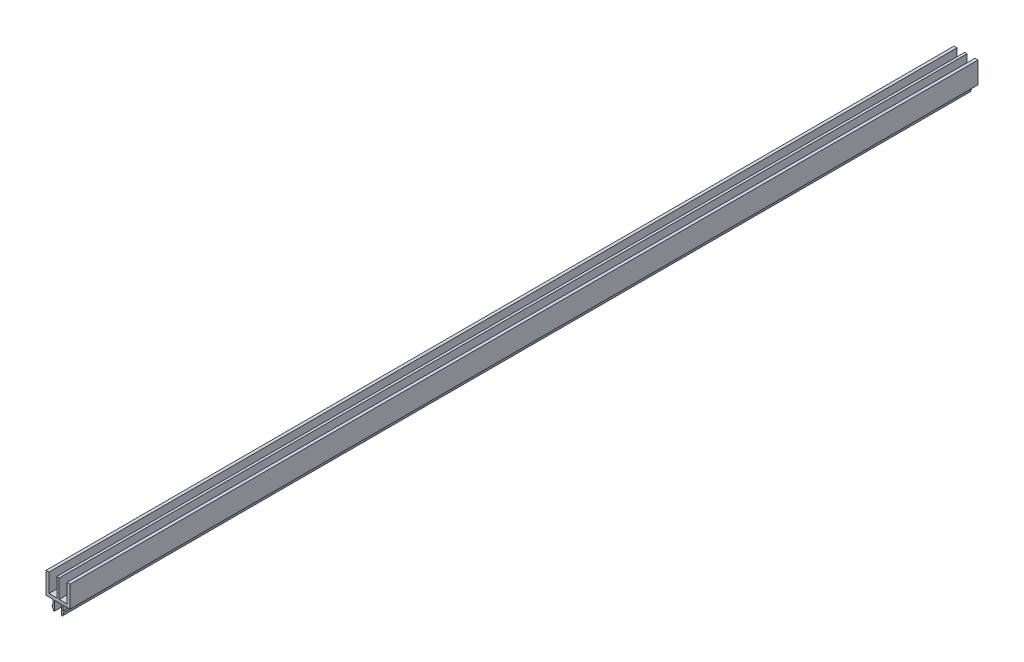
SolidWorks part; units mm, degrees
ref_plane "Plan de face" through (0, 0, 0) normal (0, 0, 1) x (1, 0, 0)
ref_plane "Plan de dessus" through (0, 0, 0) normal (0, 1, 0) x (1, 0, 0)
ref_plane "Plan de droite" through (0, 0, 0) normal (1, 0, 0) x (0, 0, -1)
ref_plane "Plan1" through (0, 0, 50) normal (0, 0, 1) x (1, 0, 0)
sketch "Esquisse1" plane through (0, 0, 50) normal (0, 0, 1) x (1, 0, 0)
  line L0 (-1, 2.5) -> (-7.5, 2.5)
  line L1 (-7.5, 2.5) -> (-7.5, 18)
  line L2 (-7.5, 18) -> (-10, 18)
  line L3 (-10, 18) -> (-10, 0)
  line L4 (-10, 0) -> (-4, 0)
  line L5 (-4, 0) -> (-4, -4.5)
  line L6 (-4, -4.5) -> (-5, -4.5)
  line L7 (-5, -4.5) -> (-3.75, -8)
  line L8 (-3.75, -8) -> (-3, -8)
  line L9 (-3, -8) -> (-3, 0)
  line L10 (-3, 0) -> (3, 0)
  line L11 (3, 0) -> (3, -8)
  line L12 (3, -8) -> (3.75, -8)
  line L13 (3.75, -8) -> (5, -4.5)
  line L14 (5, -4.5) -> (4, -4.5)
  line L15 (4, -4.5) -> (4, 0)
  line L16 (4, 0) -> (10, 0)
  line L17 (10, 0) -> (10, 18)
  line L18 (10, 18) -> (7.5, 18)
  line L19 (7.5, 18) -> (7.5, 2.5)
  line L20 (7.5, 2.5) -> (1, 2.5)
  line L21 (1, 2.5) -> (1, 18)
  line L22 (1, 18) -> (-1, 18)
  line L23 (-1, 18) -> (-1, 2.5)
extrude "Boss.-Extru.1" add sketch "Esquisse1" against normal blind 756
